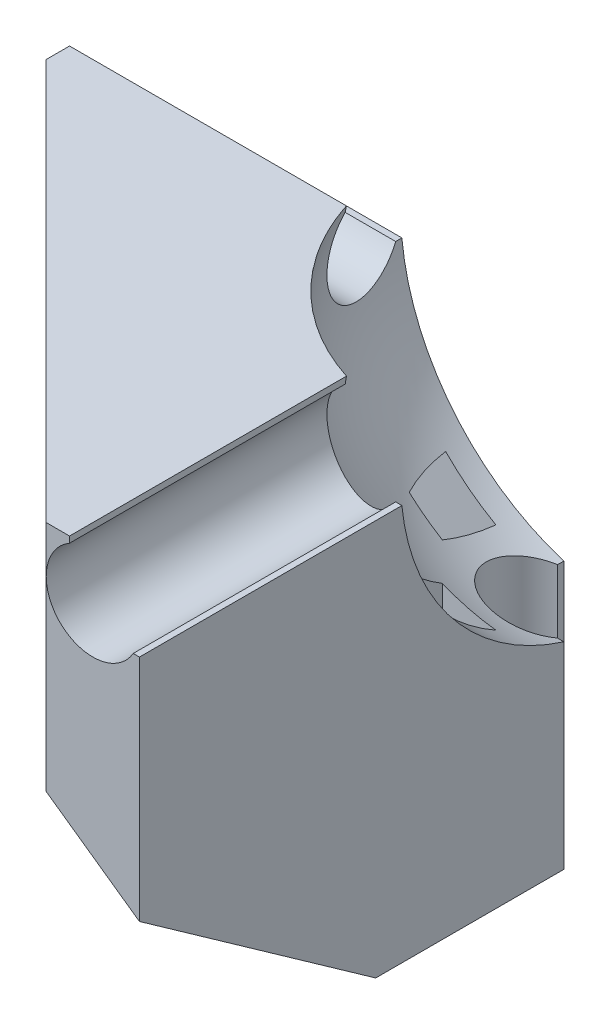
SolidWorks part; units mm, degrees
material "ABS"
ref_plane "前基準面" through (0, 0, 0) normal (0, 0, 1) x (1, 0, 0)
ref_plane "上基準面" through (0, 0, 0) normal (0, 1, 0) x (1, 0, 0)
ref_plane "右基準面" through (0, 0, 0) normal (1, 0, 0) x (0, 0, -1)
sketch "草圖1" plane through (0, 0, 0) normal (0, 1, 0) x (1, 0, 0)
  line L0 (0, -4) -> (0, -21.2132)
  line L1 (0, -21.2132) -> (-4, -21.2132)
  line L2 (-4, -21.2132) -> (-21.2132, -4)
  line L3 (-21.2132, -4) -> (-21.2132, 0)
  line L4 (-21.2132, 0) -> (-4, 0)
  line L5 (-4, 0) -> (0, 0) construction
  line L6 (0, -4) -> (0, 0) construction
  line L7 (0, -2) -> (-2, -2) construction
  line L8 (-2, -2) -> (-2, 0) construction
  line L11 (-3, -0.2679) -> (-3, 0)
  line L12 (-3, 0) -> (-4, 0)
  line L13 (-0.2679, -3) -> (0, -3)
  line L14 (0, -3) -> (0, -4)
  arc A1 (-0.2679, -3) -> (-3, -0.2679) centre (-2, -2) cw
  dimension "D3" = 4
  dimension "D4" = 2
  dimension "D1" = 30
  dimension "D2" = 4
  dimension "D5" = 1
extrude "填料-伸長1" add sketch "草圖1" along normal blind 20
sketch "草圖2" plane through (0, 20, 0) normal (0, 1, 0) x (1, 0, 0)
  line L0 (0, -21.2132) -> (0, 0)
  line L1 (0, 0) -> (-21.2132, 0)
  line L2 (-21.2132, 0) -> (-21.2132, -4)
  line L3 (-21.2132, 0) -> (-21.2132, -4) construction
  line L4 (-21.2132, -4) -> (-4, -4)
  line L5 (-4, -4) -> (-4, -21.2132)
  line L6 (-4, -21.2132) -> (0, -21.2132) construction
  line L7 (-4, -21.2132) -> (0, -21.2132)
  dimension "D1" = 4
extrude "除料-伸長1" [suppressed] cut sketch "草圖2" against normal blind 4
fillet "圓角1" [suppressed] radius 2
chamfer "導角1" distance 10 angle 45 1 edges at (-12.6066, 0, 12.6066)
sketch "草圖3" plane through (-21.2132, 0, 0) normal (-1, 0, 0) x (0, 0, 1)
  line L0 (3, 19.7321) -> (3, 20)
  line L1 (0, 20) -> (4, 20) construction
  line L2 (3, 20) -> (0, 20)
  line L3 (0, 20) -> (0, 17)
  line L4 (0, 20) -> (0, 7.1716) construction
  line L5 (0, 17) -> (0.2679, 17)
  arc A0 (3, 19.7321) -> (0.2679, 17) centre (2, 18) cw
  dimension "D2" = 2
  dimension "D1" = 2
  dimension "D3" = 3
extrude "除料-伸長2" cut sketch "草圖3" against normal up to next
ref_plane "平面1" through (0, 0, 0) normal (0.7071, 0, 0.7071) x (0.7071, 0, -0.7071)
mirror "鏡射1" about plane through (0, 0, 0) normal (0.7071, 0, 0.7071) of "除料-伸長2"
sketch "草圖4" plane through (0, 0, 0) normal (0, -1, 0) x (1, 0, 0)
  line L0 (0, 11.0711) -> (0, 3) construction
  line L5 (-1, 4.9132) -> (-3.3, 4.9132)
  line L6 (-1, 4.9132) -> (-1, 10.2132)
  line L7 (-1, 10.2132) -> (-3.3, 10.2132)
  line L8 (-3.3, 4.9132) -> (-3.3, 10.2132)
  line L9 (-4, 21.2132) -> (0, 21.2132) construction
  dimension "D1" = 5.3
  dimension "D2" = 2.3
  dimension "D3" = 1
  dimension "D4" = 11
extrude "除料-伸長3" cut sketch "草圖4" against normal blind 11
mirror "鏡射2" about plane through (0, 0, 0) normal (0.7071, 0, 0.7071) of "除料-伸長3"
ref_plane "平面2" through (0, 18, 0) normal (0, 1, 0) x (1, 0, 0)
sketch "草圖5" plane through (0, 18, 0) normal (0, 1, 0) x (1, 0, 0)
  line L0 (-3, 0) -> (-21.2132, 0) construction
  line L1 (10, 0) -> (-10, 0)
  arc A0 (-10, 0) -> (10, 0) centre (0, 0) ccw
  dimension "D1" = 10
revolve "除料-旋轉1" cut sketch "草圖5" angle 360 about L1
